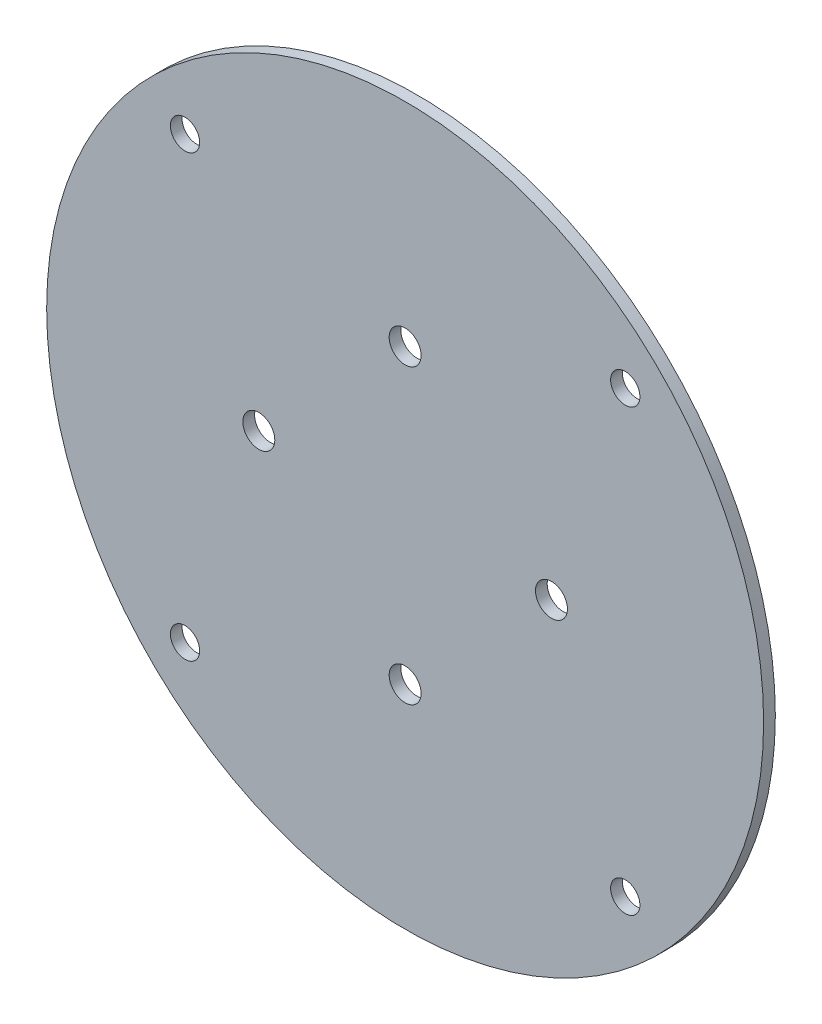
SolidWorks part; units mm, degrees
ref_plane "Front Plane" through (0, 0, 0) normal (0, 0, 1) x (1, 0, 0)
ref_plane "Top Plane" through (0, 0, 0) normal (0, 1, 0) x (1, 0, 0)
ref_plane "Right Plane" through (0, 0, 0) normal (1, 0, 0) x (0, 0, -1)
sketch "Sketch2" plane through (0, 0, 0) normal (0, 0, 1) x (1, 0, 0)
  line L0 (20, 0) -> (20, 16.1509) construction
  line L1 (0, 20) -> (-19.1479, 20) construction
  line L2 (-20, 0) -> (-20, 17.3971) construction
  line L3 (0, -20) -> (22.3917, -20) construction
  line L4 (0, 20) -> (-20.9516, 40.9516)
  line L5 (0, 20) -> (20.9516, 40.9516)
  line L6 (0, 0) -> (0, 59.0315) construction
  line L7 (0, 0) -> (60.9979, 0) construction
  line L8 (20, 0) -> (40.9516, 20.9516)
  line L9 (20, 0) -> (40.9516, -20.9516)
  line L10 (-20, 0) -> (-40.9516, 20.9516)
  line L11 (-20, 0) -> (-40.9516, -20.9516)
  line L12 (0, -20) -> (-20.9516, -40.9516)
  line L13 (0, -20) -> (20.9516, -40.9516)
  line L14 (-35.8697, 28.7987) -> (-30.4056, 23.3345)
  line L15 (-30.4056, 23.3345) -> (-23.3345, 30.4056)
  line L16 (-23.3345, 30.4056) -> (-28.7987, 35.8697)
  line L17 (0, 0) -> (-47.992, 47.992) construction
  line L18 (0, 0) -> (52.7868, 52.7868) construction
  circle A0 centre (0, 20) radius 14
  circle A1 centre (20, 0) radius 14
  circle A2 centre (0, -20) radius 14
  circle A3 centre (-20, 0) radius 14
  circle A4 centre (-15, 20) radius 1
  circle A5 centre (15, 20) radius 1.0367
  circle A6 centre (20, 15) radius 1
  circle A7 centre (20, -15) radius 1
  circle A8 centre (15, -20) radius 1
  circle A9 centre (-15, -20) radius 1
  circle A10 centre (-20, 15) radius 1
  circle A11 centre (-20, -15) radius 1
  circle A12 centre (0, 0) radius 46
  circle A13 centre (0, 20) radius 2.5
  circle A14 centre (-20, 0) radius 2.5
  circle A15 centre (20, 0) radius 2.5
  circle A16 centre (0, -20) radius 2.5
  point P39 (0, 46)
  point P63 (-26.8701, 26.8701)
  point P65 (-32.5269, 32.5269)
  dimension "D1" = 28
  dimension "D2" = 28
  dimension "D3" = 28
  dimension "D4" = 28
  dimension "D5" = 2
  dimension "D6" = 2
  dimension "D7" = 2.0734
  dimension "D8" = 2
  dimension "D9" = 2
  dimension "D10" = 2
  dimension "D11" = 2
  dimension "D12" = 2
  dimension "D17" = 15
  dimension "D26" = 5
  dimension "D27" = 5
  dimension "D28" = 5
  dimension "D29" = 5
  dimension "D13" = 15
  dimension "D14" = 15
  dimension "D15" = 15
  dimension "D16" = 15
  dimension "D18" = 15
  dimension "D19" = 15
  dimension "D20" = 15
  dimension "D21" = 26
  dimension "D22" = 45
  dimension "D23" = 45
  dimension "D24" = 45
  dimension "D25" = 45
  dimension "D30" = 45
  dimension "D31" = 45
  dimension "D32" = 10
  dimension "D33" = 8
sketch "Sketch3" plane through (0, 0, 0) normal (0, 0, 1) x (1, 0, 0)
  circle A0 centre (0, 0) radius 49
  dimension "D1" = 98
extrude "Boss-Extrude1" add sketch "Sketch3" along normal blind 1.6
sketch "Sketch4" plane through (0, 0, 0) normal (0, 0, 1) x (1, 0, 0)
  line L0 (141421.3562, -141421.3562) -> (-141469.3482, 141469.3482) construction
  line L1 (-141421.3562, -141421.3562) -> (141474.143, 141474.143) construction
  circle A0 centre (0, 0) radius 42.55 construction
  point P0 (-30.0874, 30.0874)
  point P1 (30.0874, 30.0874)
  point P4 (30.0874, -30.0874)
  point P7 (-30.0874, -30.0874)
  dimension "D1" = 85.1
hole_wizard "Ø4.0mm Clearance Dowel Hole1" positions "Sketch5" profile "Sketch6" hole size "Ø4.0" standard "ANSI Metric" end condition through all
sketch "Sketch5" plane through (0, 0, 0) normal (0, 0, 1) x (1, 0, 0)
  point P0 (-30.0874, 30.0874)
  point P3 (30.0874, 30.0874)
  point P6 (30.0874, -30.0874)
  point P9 (-30.0874, -30.0874)
sketch "Sketch6" plane through (-30.0874, 30.0874, 0) normal (1, 0, 0) x (0, 1, 0)
  line L0 (0, 0) -> (0, 1.6)
  line L1 (0, 1.6) -> (2, 1.6)
  line L2 (2, 1.6) -> (2, 0)
  line L5 (2, 0) -> (0, 0)
  line L11 (0, -6.35) -> (0, 107.95) construction
  dimension "Thru Hole Dia." = 4
  dimension "Thru Hole Depth" = 1.6
sketch "Sketch7" plane through (0, 0, 0) normal (0, 0, 1) x (1, 0, 0)
  circle A0 centre (0, 20) radius 2.1831
  circle A1 centre (20, 0) radius 2.1831
  circle A2 centre (0, -20) radius 2.1831
  circle A3 centre (-20, 0) radius 2.1831
  dimension "D1" = 4.3663
  dimension "D2" = 4.3663
  dimension "D3" = 4.3663
  dimension "D4" = 4.3663
extrude "Cut-Extrude1" cut sketch "Sketch7" along normal through all
